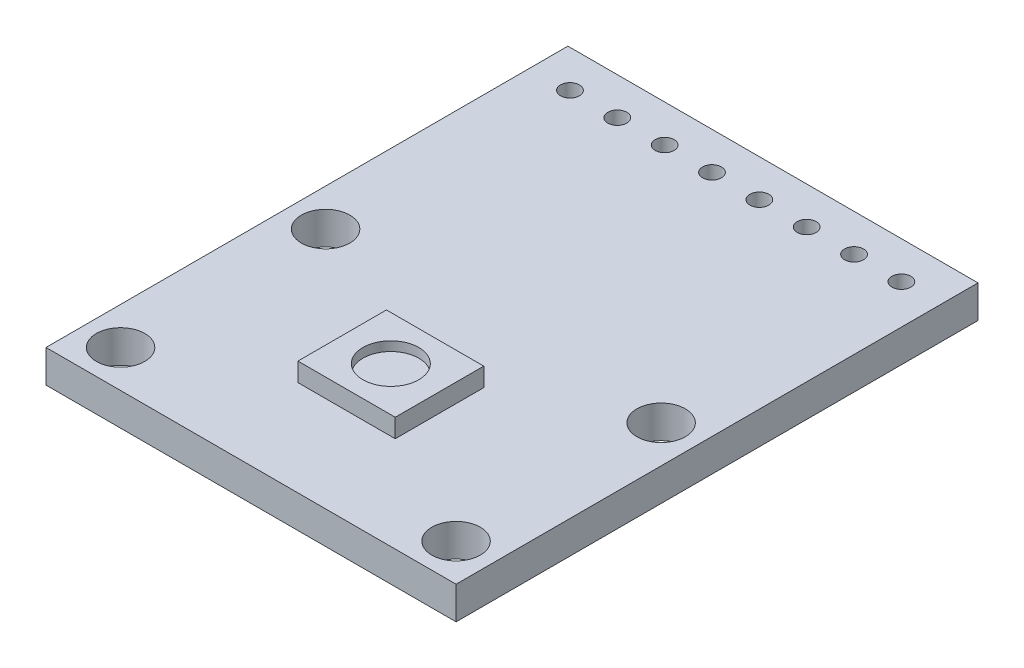
SolidWorks part; units mm, degrees
material "S-Glass Fiber"
ref_plane "Front Plane" through (0, 0, 0) normal (0, 0, 1) x (1, 0, 0)
ref_plane "Top Plane" through (0, 0, 0) normal (0, 1, 0) x (1, 0, 0)
ref_plane "Right Plane" through (0, 0, 0) normal (1, 0, 0) x (0, 0, -1)
sketch "Sketch1" plane through (0, 0, 0) normal (0, 1, 0) x (1, 0, 0)
  line L0 (0, 20.5) -> (0, -7.5) construction
  line L1 (-11, 20.5) -> (11, 20.5)
  line L2 (-11, 20.5) -> (-11, -7.5)
  line L3 (-11, -7.5) -> (11, -7.5)
  line L4 (11, 20.5) -> (11, -7.5)
  line L5 (-9, -5.5) -> (-9, -7.5) construction
  line L6 (-9, 5.5) -> (9, 5.5) construction
  line L7 (-9, 5.5) -> (-9, -5.5) construction
  line L8 (-9, -5.5) -> (9, -5.5) construction
  line L9 (9, 5.5) -> (9, -5.5) construction
  line L10 (-9, 5.5) -> (9, -5.5) construction
  line L11 (-9, -5.5) -> (9, 5.5) construction
  line L12 (-9, -5.5) -> (-11, -5.5) construction
  line L13 (-11, 18.5) -> (11, 18.5) construction
  line L14 (1.27, 18.5) -> (-1.27, 18.5) construction
  line L15 (-1.27, 18.5) -> (1.27, 18.5) construction
  line L16 (-1.27, 18.5) -> (0, 20.5) construction
  line L17 (0, 20.5) -> (1.27, 18.5) construction
  circle A0 centre (-9, 5.5) radius 1.3
  circle A1 centre (9, 5.5) radius 1.3
  circle A2 centre (9, -5.5) radius 1.3
  circle A3 centre (-9, -5.5) radius 1.3
  circle A4 centre (-8.89, 18.5) radius 0.508
  circle A5 centre (-6.35, 18.5) radius 0.508
  circle A6 centre (-3.81, 18.5) radius 0.508
  circle A7 centre (-1.27, 18.5) radius 0.508
  circle A8 centre (1.27, 18.5) radius 0.508
  circle A9 centre (3.81, 18.5) radius 0.508
  circle A10 centre (6.35, 18.5) radius 0.508
  circle A11 centre (8.89, 18.5) radius 0.508
  point P6 (0, 0)
  point P22 (1.8322, 18.5)
  point P23 (0, 6.5)
  dimension "D5" = 2.6
  dimension "D7" = 1.016
  dimension "D9" = 2.54
  dimension "D1" = 22
  dimension "D2" = 28
  dimension "D3" = 18
  dimension "D4" = 11
  dimension "D6" = 2
  dimension "D8" = 8
extrude "Boss-Extrude1" add sketch "Sketch1" along normal blind 1.75
sketch "Sketch2" plane through (0, 1.75, 0) normal (0, 1, 0) x (1, 0, 0)
  line L1 (-2.61, 2.375) -> (2.61, 2.375)
  line L2 (-2.61, 2.375) -> (-2.61, -2.375)
  line L3 (-2.61, -2.375) -> (2.61, -2.375)
  line L4 (2.61, 2.375) -> (2.61, -2.375)
  line L5 (-2.61, 2.375) -> (2.61, -2.375) construction
  line L6 (-2.61, -2.375) -> (2.61, 2.375) construction
  point P0 (0, 0)
  dimension "D1" = 5.22
  dimension "D2" = 4.75
extrude "Boss-Extrude2" add sketch "Sketch2" along normal blind 1
sketch "Sketch3" plane through (0, 2.75, 0) normal (0, 1, 0) x (1, 0, 0)
  circle A0 centre (0, 0) radius 1.5
  dimension "D1" = 3
extrude "Cut-Extrude1" cut sketch "Sketch3" against normal blind 0.5
